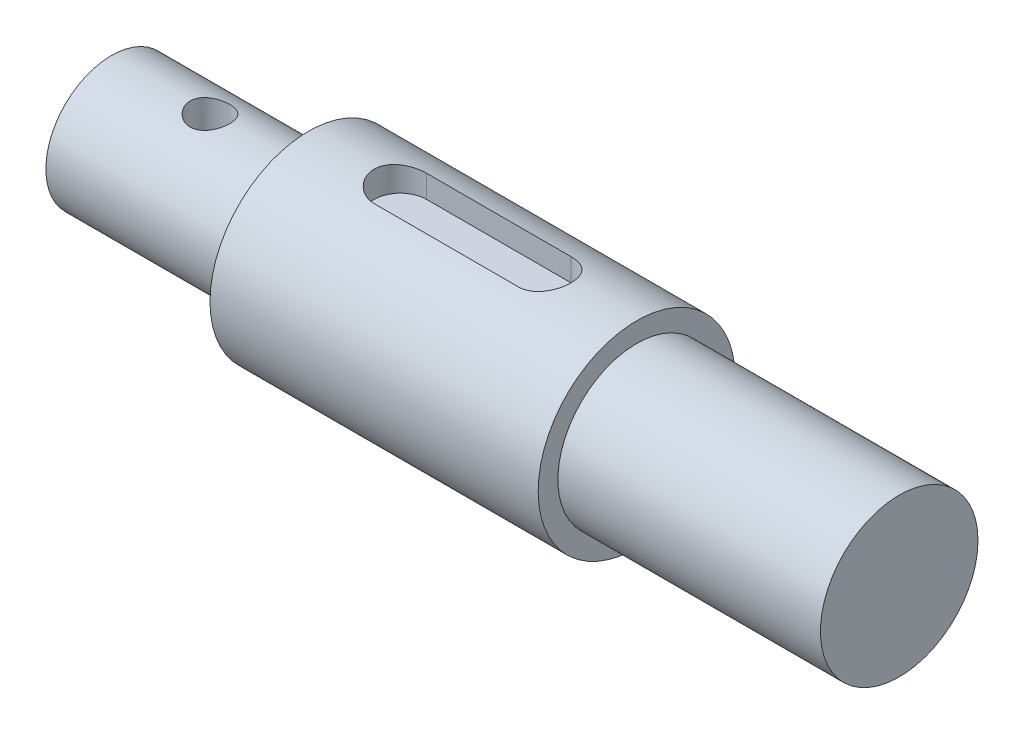
SolidWorks part; units mm, degrees
ref_plane "前视基准面" through (0, 0, 0) normal (0, 0, 1) x (1, 0, 0)
ref_plane "上视基准面" through (0, 0, 0) normal (0, 1, 0) x (1, 0, 0)
ref_plane "右视基准面" through (0, 0, 0) normal (1, 0, 0) x (0, 0, -1)
sketch "草图1" plane through (0, 0, 0) normal (1, 0, 0) x (0, 0, -1)
  circle A0 centre (0, 0) radius 10
extrude "凸台-拉伸1" add sketch "草图1" along normal blind 30
ref_plane "基准面1" through (30, 0, 0) normal (1, 0, 0) x (0, 0, -1)
sketch "草图2" plane through (30, 0, 0) normal (1, 0, 0) x (0, 0, -1)
  circle A0 centre (0, 0) radius 15
extrude "凸台-拉伸2" add sketch "草图2" along normal blind 50
ref_plane "基准面2" through (80, 0, 0) normal (1, 0, 0) x (0, 0, -1)
sketch "草图3" plane through (80, 0, 0) normal (1, 0, 0) x (0, 0, -1)
  circle A0 centre (0, 0) radius 12
extrude "凸台-拉伸3" add sketch "草图3" along normal blind 40
ref_plane "基准面3" through (0, 15, 0) normal (0, 1, 0) x (1, 0, 0)
sketch "草图4" plane through (0, 15, 0) normal (0, 1, 0) x (1, 0, 0)
  line L0 (44, 4) -> (66, 4)
  line L1 (66, -4) -> (44, -4)
  arc A0 (66, 4) -> (66, -4) centre (66, 0) cw
  arc A1 (44, -4) -> (44, 4) centre (44, 0) cw
extrude "切除-拉伸1" cut sketch "草图4" against normal blind 4
sketch "草图5" plane through (0, 0, 0) normal (0, 1, 0) x (1, 0, 0)
  circle A0 centre (15, 0) radius 3
extrude "切除-拉伸2" cut sketch "草图5" against normal mid plane 242
